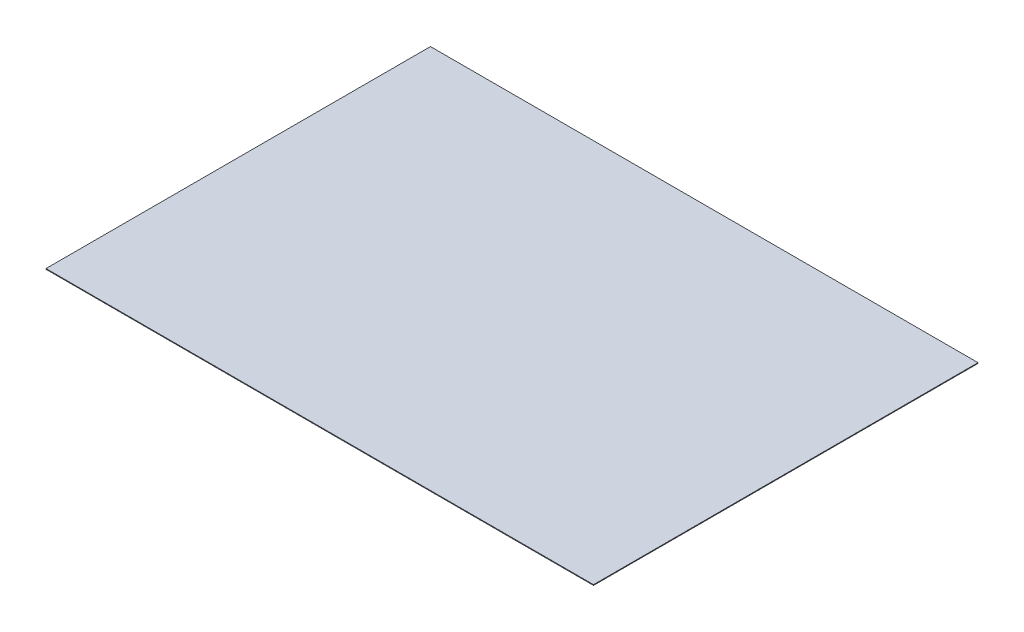
SolidWorks part; units mm, degrees
ref_plane "Alzado" through (0, 0, 0) normal (0, 0, 1) x (1, 0, 0)
ref_plane "Planta" through (0, 0, 0) normal (0, 1, 0) x (1, 0, 0)
ref_plane "Vista lateral" through (0, 0, 0) normal (1, 0, 0) x (0, 0, -1)
sketch "Croquis1" plane through (0, 0, 0) normal (0, 1, 0) x (1, 0, 0)
  line L1 (783.25, -550) -> (-783.25, -550)
  line L2 (783.25, -550) -> (783.25, 550)
  line L3 (783.25, 550) -> (-783.25, 550)
  line L4 (-783.25, -550) -> (-783.25, 550)
  line L5 (783.25, -550) -> (-783.25, 550) construction
  line L6 (783.25, 550) -> (-783.25, -550) construction
  point P0 (0, 0)
  dimension "D1" = 1566.5
  dimension "D2" = 1100
extrude "Extruir1" add sketch "Croquis1" along normal blind 2
